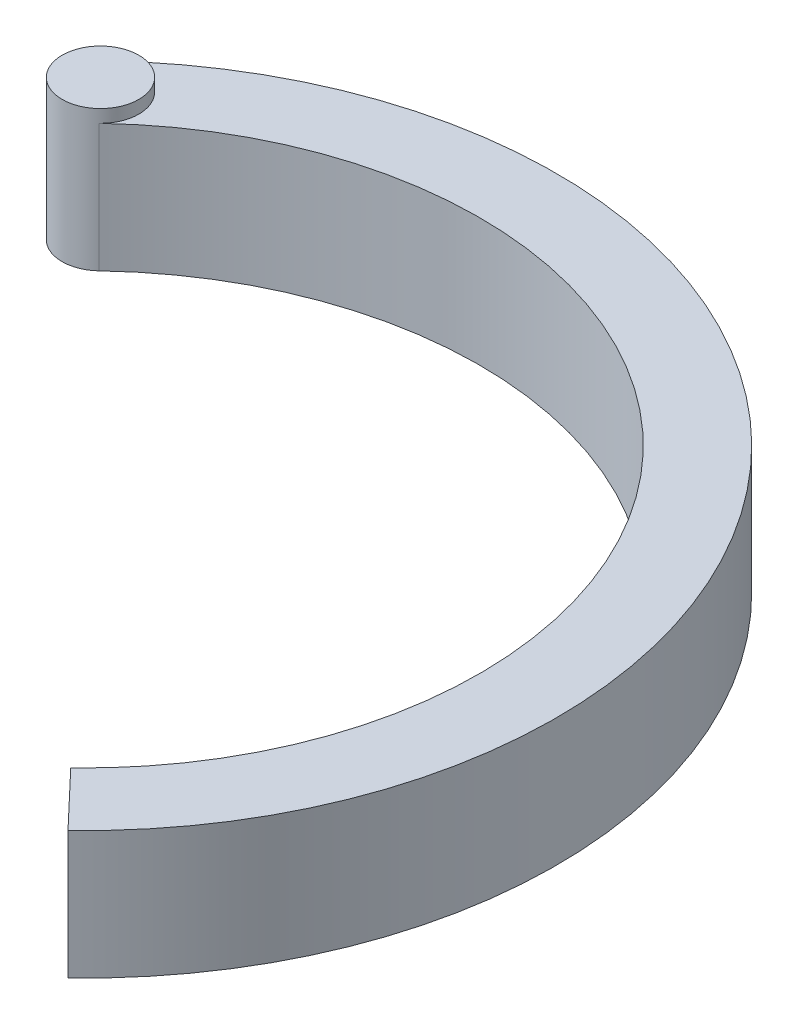
SolidWorks part; units mm, degrees
ref_plane "Front Plane" through (0, 0, 0) normal (0, 0, 1) x (1, 0, 0)
ref_plane "Top Plane" through (0, 0, 0) normal (0, 1, 0) x (1, 0, 0)
ref_plane "Right Plane" through (0, 0, 0) normal (1, 0, 0) x (0, 0, -1)
sketch "Sketch15" plane through (0, 0, 0) normal (0, 1, 0) x (1, 0, 0)
  arc A0 (0, 0) -> (46.7084, -49.1443) centre (23.3542, -24.5722) cw construction
  arc A1 (48.7751, -51.3189) -> (-2.0667, 2.1745) centre (23.3542, -24.5722) ccw
  arc A2 (44.6417, -46.9698) -> (2.0667, -2.1745) centre (23.3542, -24.5722) ccw
  arc A3 (44.6417, -46.9698) -> (48.7751, -51.3189) centre (46.7084, -49.1443) ccw
  arc A4 (-2.0667, 2.1745) -> (2.0667, -2.1745) centre (0, 0) ccw
  point P3 (47.9264, -1.218)
extrude "Boss-Extrude8" add sketch "Sketch15" along normal blind 10
sketch "Sketch17" plane through (0, 10, 0) normal (0, 1, 0) x (1, 0, 0)
  circle A0 centre (0, 0) radius 3
extrude "Boss-Extrude9" add sketch "Sketch17" along normal blind 1
sketch "Sketch18" plane through (0, 10, 0) normal (0, 1, 0) x (1, 0, 0)
  line L0 (44.6417, -46.9698) -> (48.7751, -51.3189)
  arc A0 (48.7751, -51.3189) -> (44.5339, -51.2111) centre (46.7084, -49.1443) cw
  arc A1 (44.6417, -46.9698) -> (48.7751, -51.3189) centre (46.7084, -49.1443) ccw construction
  arc A2 (44.5339, -51.2111) -> (44.6417, -46.9698) centre (46.7084, -49.1443) cw
extrude "Cut-Extrude3" cut sketch "Sketch18" against normal blind 52 and the other way blind 48
